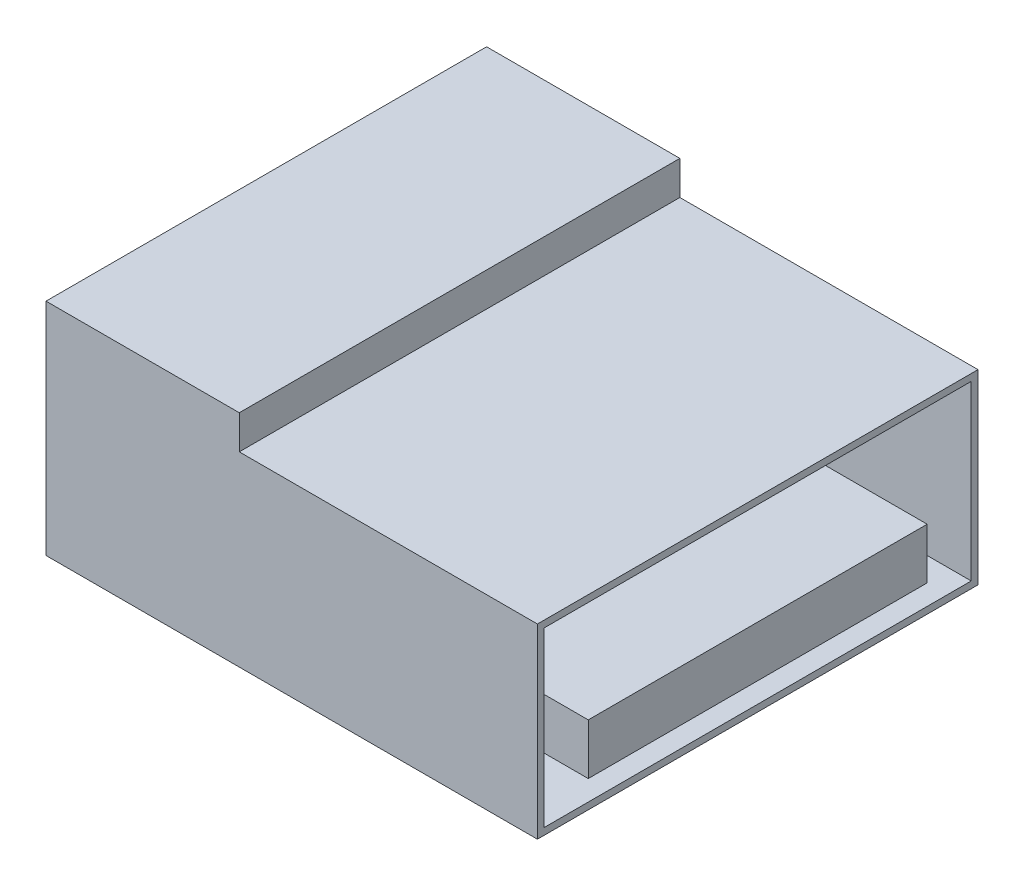
SolidWorks part; units mm, degrees
ref_plane "前视基准面" through (0, 0, 0) normal (0, 0, 1) x (1, 0, 0)
ref_plane "上视基准面" through (0, 0, 0) normal (0, 1, 0) x (1, 0, 0)
ref_plane "右视基准面" through (0, 0, 0) normal (1, 0, 0) x (0, 0, -1)
sketch "草图1" plane through (0, 0, 0) normal (0, 1, 0) x (1, 0, 0)
  line L1 (-8.5812, 4.4886) -> (5.9188, 4.4886)
  line L2 (-8.5812, 4.4886) -> (-8.5812, -8.5114)
  line L3 (-8.5812, -8.5114) -> (5.9188, -8.5114)
  line L4 (5.9188, 4.4886) -> (5.9188, -8.5114)
  line L5 (-8.5812, 4.4886) -> (5.9188, -8.5114) construction
  line L6 (-8.5812, -8.5114) -> (5.9188, 4.4886) construction
  point P4 (-1.3312, -2.0114)
  dimension "D1" = 14.5
  dimension "D2" = 13
extrude "凸台-拉伸1" add sketch "草图1" along normal blind 5.5
sketch "草图2" plane through (0, 5.5, 0) normal (0, 1, 0) x (1, 0, 0)
  line L0 (-8.5812, -8.5114) -> (5.9188, -8.5114) construction
  line L1 (-8.5812, 4.4886) -> (-2.878, 4.4886)
  line L2 (-8.5812, 4.4886) -> (-8.5812, -8.5114)
  line L3 (-8.5812, -8.5114) -> (-2.878, -8.5114)
  line L4 (-2.878, 4.4886) -> (-2.878, -8.5114)
  line L5 (-8.5812, 4.4886) -> (-2.878, -8.5114) construction
  line L6 (-8.5812, -8.5114) -> (-2.878, 4.4886) construction
  point P4 (-5.7296, -2.0114)
extrude "凸台-拉伸2" add sketch "草图2" along normal blind 1
sketch "草图3" plane through (5.9188, 0, 0) normal (1, 0, 0) x (0, 0, -1)
  line L0 (-8.5114, 5.5) -> (-8.5114, 0) construction
  line L1 (-8.3114, 5.3) -> (4.2886, 5.3)
  line L2 (-8.3114, 5.3) -> (-8.3114, 0.2)
  line L3 (-8.3114, 0.2) -> (4.2886, 0.2)
  line L4 (4.2886, 5.3) -> (4.2886, 0.2)
  line L5 (-8.3114, 5.3) -> (4.2886, 0.2) construction
  line L6 (-8.3114, 0.2) -> (4.2886, 5.3) construction
  line L7 (-8.5114, 0) -> (4.4886, 0) construction
  line L8 (-8.5114, 5.5) -> (4.4886, 5.5) construction
  line L9 (4.4886, 5.5) -> (4.4886, 0) construction
  point P4 (-2.0114, 2.75)
  dimension "D1" = 0.2
  dimension "D2" = 0.2
  dimension "D3" = 0.2
  dimension "D4" = 0.2
extrude "切除-拉伸1" cut sketch "草图3" against normal blind 9.5
sketch "草图4" plane through (-3.5812, 0, 0) normal (1, 0, 0) x (0, 0, -1)
  line L0 (4.2886, 5.3) -> (-8.3114, 5.3) construction
  line L1 (-7.0114, 2.3) -> (2.9886, 2.3)
  line L2 (-7.0114, 2.3) -> (-7.0114, 0.8)
  line L3 (-7.0114, 0.8) -> (2.9886, 0.8)
  line L4 (2.9886, 2.3) -> (2.9886, 0.8)
  line L5 (-7.0114, 2.3) -> (2.9886, 0.8) construction
  line L6 (-7.0114, 0.8) -> (2.9886, 2.3) construction
  line L7 (-8.3114, 0.2) -> (4.2886, 0.2) construction
  point P4 (-2.0114, 1.55)
  point P5 (-2.0114, 5.3)
  dimension "D1" = 10
  dimension "D2" = 1.5
  dimension "D3" = 0.6
extrude "凸台-拉伸3" add sketch "草图4" along normal blind 9.5
